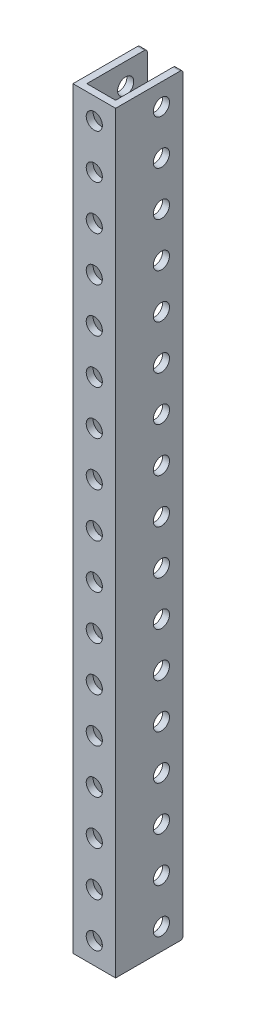
SolidWorks part; units mm, degrees
ref_plane "Front Plane" through (0, 0, 0) normal (0, 0, 1) x (1, 0, 0)
ref_plane "Top Plane" through (0, 0, 0) normal (0, 1, 0) x (1, 0, 0)
ref_plane "Right Plane" through (0, 0, 0) normal (1, 0, 0) x (0, 0, -1)
ref_plane "Plane1" through (-4.699, 0, 0) normal (-1, 0, 0) x (0, -1, 0)
sketch "Sketch1" plane through (-4.699, 0, 0) normal (-1, 0, 0) x (0, -1, 0)
  line L0 (-165.989, -13.335) -> (0, -13.335)
  line L1 (0, -13.335) -> (0, 1.524)
  line L2 (0, 1.524) -> (-165.989, 1.524)
  line L3 (-165.989, 1.524) -> (-165.989, -13.335)
extrude "Boss-Extrude1" add sketch "Sketch1" against normal blind 9.398
sketch "Sketch2" plane through (0, 0, 0) normal (0, -1, 0) x (1, 0, 0)
  line L0 (-3.175, -13.335) -> (3.175, -13.335)
  line L1 (3.175, -13.335) -> (3.175, 0)
  line L2 (3.175, 0) -> (-3.175, 0)
  line L3 (-3.175, 0) -> (-3.175, -13.335)
extrude "Cut-Extrude1" cut sketch "Sketch2" against normal through all
hole_wizard "#5 Clearance Hole1" positions "Sketch4" profile "Sketch3" hole size "#5" standard "ANSI Inch"
sketch "Sketch4" plane through (4.699, 0, 0) normal (1, 0, 0) x (0, 0, -1)
  point P0 (8.5725, 151.4475)
  point P1 (8.5725, 161.2265)
  point P2 (8.5725, 141.6685)
  point P3 (8.5725, 131.8895)
  point P4 (8.5725, 122.1105)
  point P5 (8.5725, 112.3315)
  point P6 (8.5725, 102.5525)
  point P7 (8.5725, 92.7735)
  point P8 (8.5725, 82.9945)
  point P9 (8.5725, 73.2155)
  point P10 (8.5725, 63.4365)
  point P11 (8.5725, 53.6575)
  point P12 (8.5725, 43.8785)
  point P13 (8.5725, 34.0995)
  point P14 (8.5725, 24.3205)
  point P15 (8.5725, 14.5415)
  point P16 (8.5725, 4.7625)
sketch "Sketch3" plane through (4.699, 151.4475, -8.5725) normal (0, 1, 0) x (0, 0, -1)
  line L0 (0, 0) -> (0, 1.524)
  line L1 (0, 1.524) -> (1.778, 1.524)
  line L2 (1.778, 1.524) -> (1.778, 0)
  line L5 (1.778, 0) -> (0, 0)
  line L11 (0, -6.35) -> (0, 107.95) construction
  dimension "Thru Hole Dia." = 3.556
  dimension "Thru Hole Depth" = 1.524
hole_wizard "#5 Clearance Hole2" positions "Sketch6" profile "Sketch5" hole size "#5" standard "ANSI Inch"
sketch "Sketch6" plane through (0, 0, 1.524) normal (0, 0, 1) x (1, 0, 0)
  point P0 (0, 151.4475)
  point P1 (0, 161.2265)
  point P2 (0, 141.6685)
  point P3 (0, 131.8895)
  point P4 (0, 122.1105)
  point P5 (0, 112.3315)
  point P6 (0, 102.5525)
  point P7 (0, 92.7735)
  point P8 (0, 82.9945)
  point P9 (0, 73.2155)
  point P10 (0, 63.4365)
  point P11 (0, 53.6575)
  point P12 (0, 43.8785)
  point P13 (0, 34.0995)
  point P14 (0, 24.3205)
  point P15 (0, 14.5415)
  point P16 (0, 4.7625)
sketch "Sketch5" plane through (0, 151.4475, 1.524) normal (1, 0, 0) x (0, -1, 0)
  line L0 (0, 0) -> (0, 14.859)
  line L1 (0, 14.859) -> (1.778, 14.859)
  line L2 (1.778, 14.859) -> (1.778, 0)
  line L5 (1.778, 0) -> (0, 0)
  line L11 (0, -6.35) -> (0, 107.95) construction
  dimension "Thru Hole Dia." = 3.556
  dimension "Thru Hole Depth" = 14.859
hole_wizard "#5 Clearance Hole3" positions "Sketch8" profile "Sketch7" hole size "#5" standard "ANSI Inch"
sketch "Sketch8" plane through (-3.175, 0, 0) normal (1, 0, 0) x (0, 0, -1)
  point P0 (8.5725, 151.4475)
  point P1 (8.5725, 161.2265)
  point P2 (8.5725, 141.6685)
  point P3 (8.5725, 131.8895)
  point P4 (8.5725, 122.1105)
  point P5 (8.5725, 112.3315)
  point P6 (8.5725, 102.5525)
  point P7 (8.5725, 92.7735)
  point P8 (8.5725, 82.9945)
  point P9 (8.5725, 73.2155)
  point P10 (8.5725, 63.4365)
  point P11 (8.5725, 53.6575)
  point P12 (8.5725, 43.8785)
  point P13 (8.5725, 34.0995)
  point P14 (8.5725, 24.3205)
  point P15 (8.5725, 14.5415)
  point P16 (8.5725, 4.7625)
sketch "Sketch7" plane through (-3.175, 151.4475, -8.5725) normal (0, 1, 0) x (0, 0, -1)
  line L0 (0, 0) -> (0, 1.524)
  line L1 (0, 1.524) -> (1.778, 1.524)
  line L2 (1.778, 1.524) -> (1.778, 0)
  line L5 (1.778, 0) -> (0, 0)
  line L11 (0, -6.35) -> (0, 107.95) construction
  dimension "Thru Hole Dia." = 3.556
  dimension "Thru Hole Depth" = 1.524
fillet "Fillet1" radius 0.635 4 edges at (3.937, 0, -13.335) (3.937, 165.989, -13.335) (-3.937, 165.989, -13.335) (-3.937, 0, -13.335)
